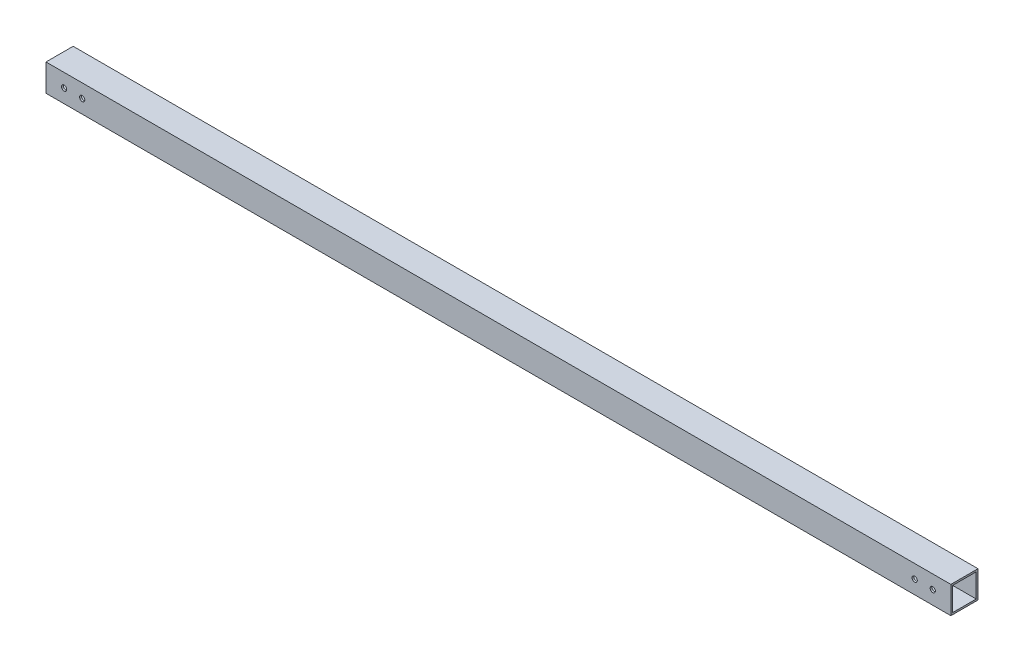
SolidWorks part; units mm, degrees
material "Thornel Mat VMA"
ref_plane "前视基准面" through (0, 0, 0) normal (0, 0, 1) x (1, 0, 0)
ref_plane "上视基准面" through (0, 0, 0) normal (0, 1, 0) x (1, 0, 0)
ref_plane "右视基准面" through (0, 0, 0) normal (1, 0, 0) x (0, 0, -1)
other "Configuration Table"
sketch "草图1" plane through (0, 0, 0) normal (1, 0, 0) x (0, 0, -1)
  line L0 (-6.5, -6.5) -> (-6.5, 6.5)
  line L1 (-7.5, -7.5) -> (7.5, -7.5)
  line L2 (-7.5, -7.5) -> (-7.5, 7.5)
  line L3 (-7.5, 7.5) -> (7.5, 7.5)
  line L4 (7.5, -7.5) -> (7.5, 7.5)
  line L5 (-7.5, -7.5) -> (7.5, 7.5) construction
  line L6 (-7.5, 7.5) -> (7.5, -7.5) construction
  line L7 (-6.5, 6.5) -> (6.5, 6.5)
  line L8 (6.5, -6.5) -> (6.5, 6.5)
  line L9 (-6.5, -6.5) -> (6.5, -6.5)
  point P0 (0, 0)
  dimension "D1" = 15
  dimension "D2" = 15
  dimension "D3" = 1
extrude "凸台-拉伸1" add sketch "草图1" along normal blind 500
sketch "草图2" plane through (0, 0, 7.5) normal (0, 0, 1) x (1, 0, 0)
  circle A0 centre (490, 0) radius 1.45 construction
  circle A1 centre (480, 0) radius 1.45 construction
  circle A2 centre (10, 0) radius 1.45 construction
  circle A3 centre (20, 0) radius 1.45 construction
  circle A4 centre (490, 0) radius 1.45
  circle A5 centre (480, 0) radius 1.45
  circle A6 centre (10, 0) radius 1.45
  circle A7 centre (20, 0) radius 1.45
extrude "切除-拉伸1" cut sketch "草图2" against normal through all
